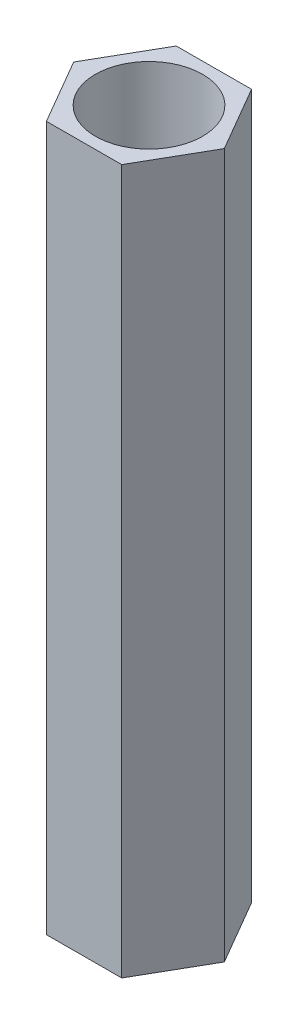
SolidWorks part; units mm, degrees
ref_plane "Front Plane" through (0, 0, 0) normal (0, 0, 1) x (1, 0, 0)
ref_plane "Top Plane" through (0, 0, 0) normal (0, 1, 0) x (1, 0, 0)
ref_plane "Right Plane" through (0, 0, 0) normal (1, 0, 0) x (0, 0, -1)
sketch "Sketch1" plane through (0, 0, 0) normal (0, 1, 0) x (1, 0, 0)
  line L1 (1.1596, -1.9971) -> (2.3094, 0.0057)
  line L2 (2.3094, 0.0057) -> (1.1498, 2.0028)
  line L3 (1.1498, 2.0028) -> (-1.1596, 1.9971)
  line L4 (-1.1596, 1.9971) -> (-2.3094, -0.0057)
  line L5 (-2.3094, -0.0057) -> (-1.1498, -2.0028)
  line L6 (-1.1498, -2.0028) -> (1.1596, -1.9971)
  circle A0 centre (0, 0) radius 2 construction
  circle A1 centre (0, 0) radius 1.65
  dimension "D1" = 4
  dimension "D2" = 3.3
extrude "Boss-Extrude1" add sketch "Sketch1" along normal blind 21.65
